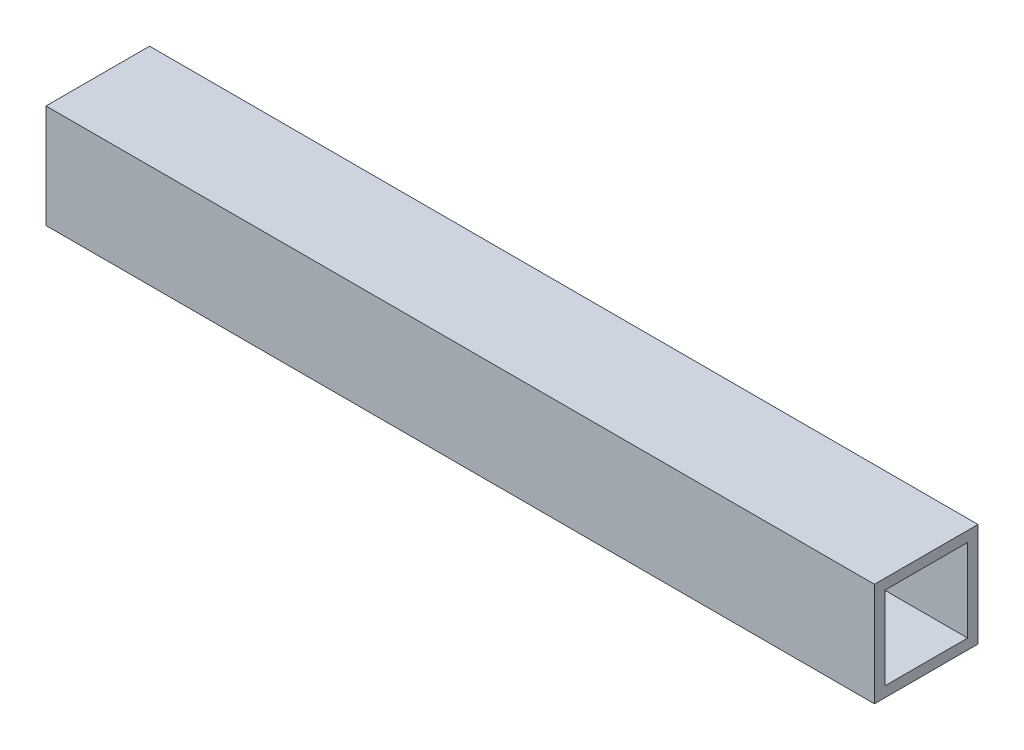
SolidWorks part; units mm, degrees
ref_plane "Front Plane" through (0, 0, 0) normal (0, 0, 1) x (1, 0, 0)
ref_plane "Top Plane" through (0, 0, 0) normal (0, 1, 0) x (1, 0, 0)
ref_plane "Right Plane" through (0, 0, 0) normal (1, 0, 0) x (0, 0, -1)
sketch "Sketch1" plane through (0, 0, 0) normal (1, 0, 0) x (0, 0, -1)
  line L0 (-10.16, 10.16) -> (10.16, 10.16)
  line L1 (-12.7, -12.7) -> (12.7, -12.7)
  line L2 (-12.7, -12.7) -> (-12.7, 12.7)
  line L3 (-12.7, 12.7) -> (12.7, 12.7)
  line L4 (12.7, -12.7) -> (12.7, 12.7)
  line L5 (-12.7, -12.7) -> (12.7, 12.7) construction
  line L6 (-12.7, 12.7) -> (12.7, -12.7) construction
  line L7 (10.16, -10.16) -> (10.16, 10.16)
  line L8 (-10.16, -10.16) -> (10.16, -10.16)
  line L9 (-10.16, -10.16) -> (-10.16, 10.16)
  point P0 (0, 0)
  dimension "D1" = 25.4
  dimension "D2" = 25.4
  dimension "D3" = 2.54
extrude "Boss-Extrude1" add sketch "Sketch1" along normal blind 203.2
